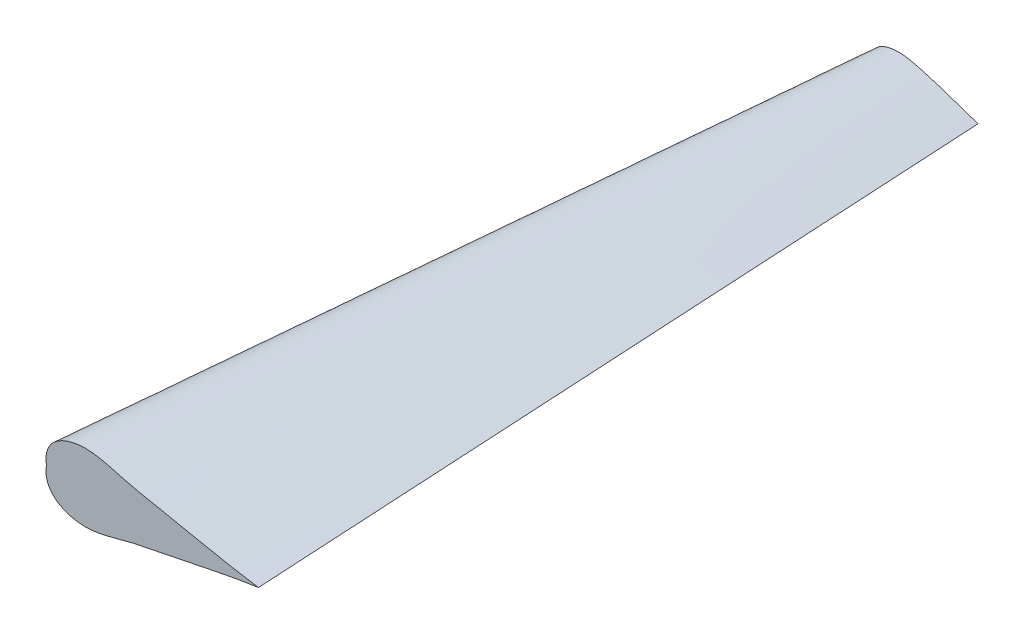
SolidWorks part; units mm, degrees
ref_plane "Front Plane" through (0, 0, 0) normal (0, 0, 1) x (1, 0, 0)
ref_plane "Top Plane" through (0, 0, 0) normal (0, 1, 0) x (1, 0, 0)
ref_plane "Right Plane" through (0, 0, 0) normal (1, 0, 0) x (0, 0, -1)
ref_plane "Plane1" through (0, 0, 1000) normal (0, 0, 1) x (1, 0, 0)
sketch "Sketch1" plane through (0, 0, 1000) normal (0, 0, 1) x (1, 0, 0)
  spline S0 degree 3 poles (0, 0) (-5.3747, 30.8984) (46.7334, 58.7828) (105.3495, 37.1004) (189.5018, 21.4887) (251.0487, 7.1028) (300, 0) knots 0 0 0 0 0.224641 0.429841 0.552694 1 1 1 1
  spline S1 degree 3 poles (0, 0) (-5.3747, -30.8984) (46.7334, -58.7828) (105.3495, -37.1004) (189.5018, -21.4887) (251.0487, -7.1028) (300, 0) knots 0 0 0 0 0.224641 0.429841 0.552694 1 1 1 1
sketch "Sketch2" plane through (0, 0, 0) normal (0, 0, 1) x (1, 0, 0)
  spline S0 degree 3 poles (168.1886, 77.3844) (164.6572, 99.4678) (197.1508, 113.6653) (252.9321, 100.5278) (291.0508, 86.7382) (318.1886, 77.3844) knots 0 0 0 0 0.300098 0.498608 1 1 1 1
  spline S1 degree 3 poles (168.1886, 77.3844) (164.6572, 55.301) (197.1508, 41.1034) (252.9321, 54.2409) (291.0508, 68.0306) (318.1886, 77.3844) knots 0 0 0 0 0.300098 0.498608 1 1 1 1
loft "Loft1" add profiles "Sketch2", "Sketch1"
sketch "Sketch3" plane through (0, 0, 1000) normal (0, 0, 1) x (1, 0, 0)
  line L0 (0, 0) -> (300, 0)
  spline S0 degree 3 poles (300, 0) (251.0487, 7.1028) (189.5018, 21.4887) (105.3495, 37.1004) (46.7334, 58.7828) (-5.3747, 30.8984) (0, 0) knots 0 0 0 0 0.447306 0.570159 0.775359 1 1 1 1 construction
  spline S1 degree 3 poles (0, 0) (-5.3747, -30.8984) (46.7334, -58.7828) (105.3495, -37.1004) (189.5018, -21.4887) (251.0487, -7.1028) (300, 0) knots 0 0 0 0 0.224641 0.429841 0.552694 1 1 1 1 construction
